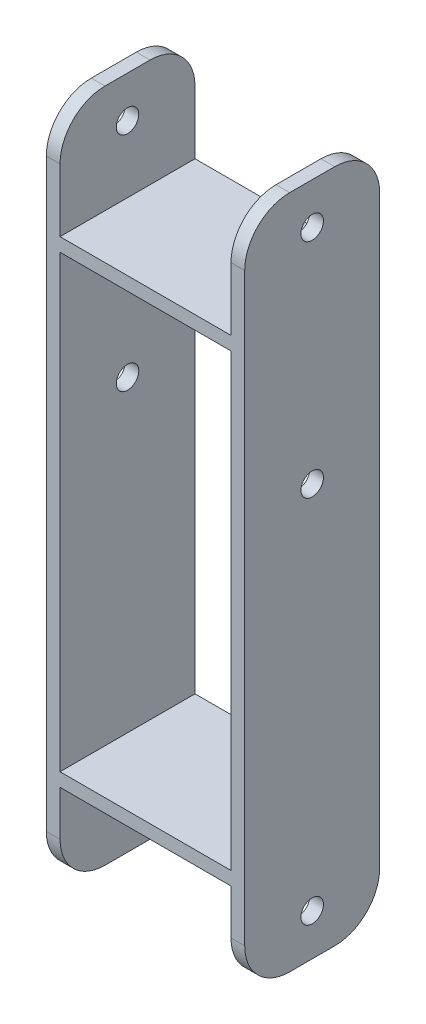
SolidWorks part; units mm, degrees
ref_plane "Front Plane" through (0, 0, 0) normal (0, 0, 1) x (1, 0, 0)
ref_plane "Top Plane" through (0, 0, 0) normal (0, 1, 0) x (1, 0, 0)
ref_plane "Right Plane" through (0, 0, 0) normal (1, 0, 0) x (0, 0, -1)
sketch "Sketch1" plane through (0, 0, 0) normal (0, 0, 1) x (1, 0, 0)
  line L0 (0, 26.1905) -> (0, -22.5714) construction
  line L1 (-22.0476, 100) -> (-19, 100)
  line L2 (-22.0476, 100) -> (-22.0476, -50)
  line L3 (-22.0476, -50) -> (-19, -50)
  line L4 (-19, 100) -> (-19, -50)
  line L5 (22.0476, -50) -> (19, -50)
  line L6 (19, 100) -> (19, -50)
  line L7 (22.0476, 100) -> (22.0476, -50)
  line L8 (22.0476, 100) -> (19, 100)
  line L10 (-19, 76) -> (19, 76)
  line L11 (-19, 76) -> (-19, 73)
  line L12 (-19, 73) -> (19, 73)
  line L13 (19, 76) -> (19, 73)
  line L14 (-19, -27) -> (19, -27)
  line L15 (-19, -27) -> (-19, -30)
  line L16 (-19, -30) -> (19, -30)
  line L17 (19, -27) -> (19, -30)
  dimension "D1" = 38
  dimension "D2" = 150
  dimension "D3" = 3.0476
  dimension "D4" = 50
  dimension "D5" = 3
  dimension "D6" = 3
  dimension "D7" = 100
  dimension "D8" = 20
extrude "Boss-Extrude1" add sketch "Sketch1" along normal mid plane 30 contours L4 L1 L2 L3 | L7 L8 L6 L5 | L10 L13 L12 L11 | L14 L17 L16 L15
fillet "Fillet1" radius 10 8 edges at (-20.5238, -50, -15) (20.5238, -50, -15) (20.5238, -50, 15) (-20.5238, -50, 15) (-20.5238, 100, 15) (-20.5238, 100, -15) (20.5238, 100, -15) (20.5238, 100, 15)
sketch "Sketch2" plane through (22.0476, 0, 0) normal (1, 0, 0) x (0, 0, -1)
  circle A0 centre (0, 41.4396) radius 2.5
  circle A1 centre (0, -40.7478) radius 2.5
  dimension "D1" = 5
  dimension "D2" = 5
extrude "Cut-Extrude1" cut sketch "Sketch2" against normal blind 61
sketch "Sketch3" plane through (22.0476, 0, 0) normal (1, 0, 0) x (0, 0, -1)
  circle A0 centre (0, 90.8245) radius 2.5
  dimension "D1" = 5
extrude "Cut-Extrude2" cut sketch "Sketch3" against normal blind 55
